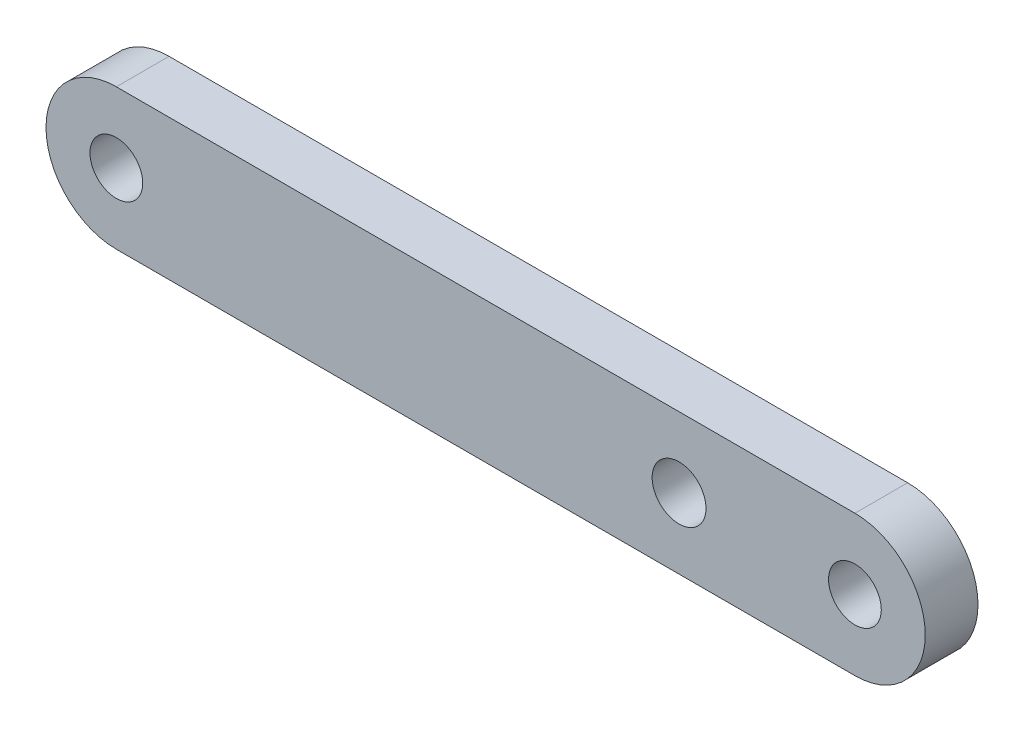
SolidWorks part; units mm, degrees
ref_plane "Front Plane" through (0, 0, 0) normal (0, 0, 1) x (1, 0, 0)
ref_plane "Top Plane" through (0, 0, 0) normal (0, 1, 0) x (1, 0, 0)
ref_plane "Right Plane" through (0, 0, 0) normal (1, 0, 0) x (0, 0, -1)
sketch "Sketch1" plane through (0, 0, 0) normal (0, 0, 1) x (1, 0, 0)
  line L0 (-125, 0) -> (125, 0) construction
  line L1 (0, -26.8125) -> (0, 26.8125) construction
  line L3 (-105, -20) -> (105, -20)
  line L5 (-105, 20) -> (105, 20)
  arc A0 (-105, 20) -> (-105, -20) centre (-105, 0) ccw
  arc A1 (105, 20) -> (105, -20) centre (105, 0) cw
  point P0 (0, 0)
  point P4 (0, 0)
  point P8 (0, 0)
  dimension "D1" = 125
  dimension "D2" = 210
  dimension "D3" = 20
extrude "Boss-Extrude1" add sketch "Sketch1" along normal blind 15
ref_plane "Plane1" through (-105, 0, 0) normal (1, 0, 0) x (0, 0, -1)
sketch "Sketch4" plane through (0, 0, 15) normal (0, 0, 1) x (1, 0, 0)
  circle A0 centre (105, 0) radius 7.5
  circle A1 centre (52.1657, 0) radius 7.5401
  dimension "D2" = 15
  dimension "D1" = 105
extrude "Cut-Extrude1" cut sketch "Sketch4" against normal through all contours A0
mirror "Mirror1" about plane through (0, 0, 0) normal (1, 0, 0) of "Cut-Extrude1"
sketch "Sketch5" plane through (0, 0, 15) normal (0, 0, 1) x (1, 0, 0)
  circle A0 centre (55, 0) radius 7.6563
  circle A1 centre (105, 0) radius 7.5 construction
  dimension "D1" = 50
extrude "Cut-Extrude2" cut sketch "Sketch5" against normal through all
